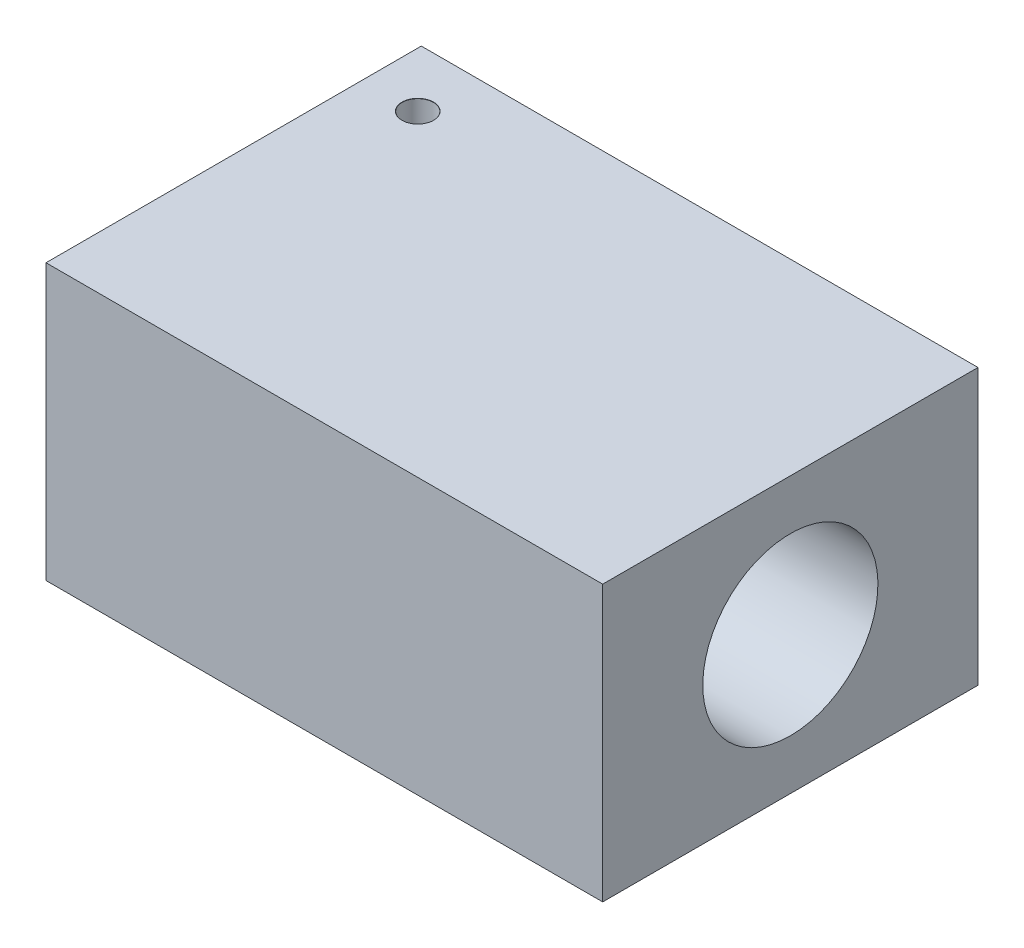
SolidWorks part; units mm, degrees
ref_plane "Front Plane" through (0, 0, 0) normal (0, 0, 1) x (1, 0, 0)
ref_plane "Top Plane" through (0, 0, 0) normal (0, 1, 0) x (1, 0, 0)
ref_plane "Right Plane" through (0, 0, 0) normal (1, 0, 0) x (0, 0, -1)
sketch "Sketch1" plane through (0, 0, 0) normal (0, 0, 1) x (1, 0, 0)
  line L1 (-44.5, 22) -> (44.5, 22)
  line L2 (-44.5, 22) -> (-44.5, -22)
  line L3 (-44.5, -22) -> (44.5, -22)
  line L4 (44.5, 22) -> (44.5, -22)
  line L5 (-44.5, 22) -> (44.5, -22) construction
  line L6 (-44.5, -22) -> (44.5, 22) construction
  point P0 (0, 0)
  dimension "D1" = 89
  dimension "D2" = 44
extrude "Boss-Extrude1" add sketch "Sketch1" along normal mid plane 60
sketch "Sketch3" plane through (-44.5, 0, 0) normal (-1, 0, 0) x (0, 0, 1)
  circle A0 centre (0, 0) radius 14
  dimension "D1" = 28
extrude "Cut-Extrude1" cut sketch "Sketch3" against normal through all
hole_wizard "Ø5.0mm Dowel Hole1" positions "Sketch6" profile "Sketch5" hole size "Ø5.0" standard "DIN" end condition up to next
sketch "Sketch6" plane through (0, 22, 0) normal (0, 1, 0) x (1, 0, 0)
  point P0 (-35.7599, 20.696)
sketch "Sketch5" plane through (-35.7599, 22, -20.696) normal (1, 0, 0) x (0, 0, 1)
  line L0 (0, 0) -> (0, 44)
  line L1 (0, 44) -> (2.5, 44)
  line L2 (2.5, 44) -> (2.5, 0.025)
  line L3 (2.5, 0.025) -> (2.525, 0)
  line L5 (2.525, 0) -> (0, 0)
  line L6 (-2.5, 0.025) -> (-2.525, 0) construction
  line L11 (0, -6.35) -> (0, 107.95) construction
  dimension "Thru Hole Dia." = 5
  dimension "Thru Hole Depth" = 44
  dimension "Near C'Sink Dia." = 5.05
  dimension "Near C'Sink Angle" = 90
equation "\"L\"= 89'duljina bloka"
equation "\"B\"= 60'širina bloka"
equation "\"H\"= 44'visina bez stopala"
equation "\"D1@Sketch1\"=\"L\""
equation "\"D2@Sketch1\"=\"H\""
equation "\"D1@Boss-Extrude1\"= \"B\""
